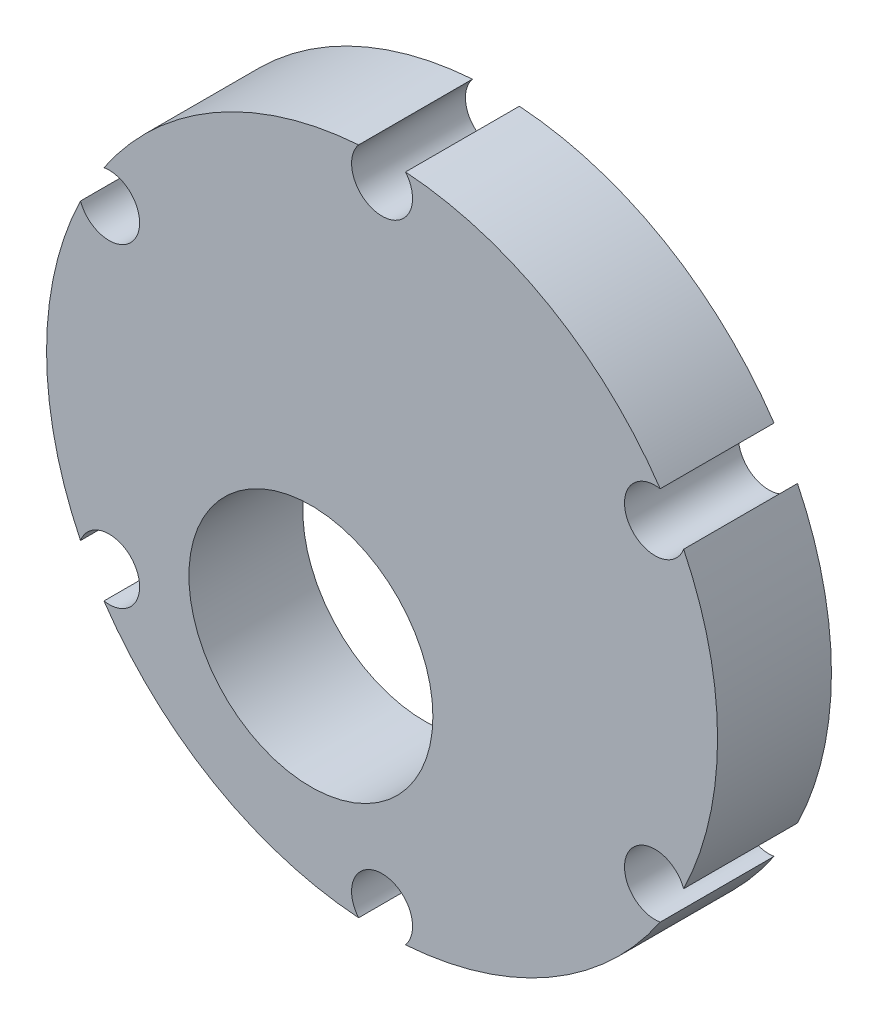
SolidWorks part; units mm, degrees
ref_plane "Front Plane" through (0, 0, 0) normal (0, 0, 1) x (1, 0, 0)
ref_plane "Top Plane" through (0, 0, 0) normal (0, 1, 0) x (1, 0, 0)
ref_plane "Right Plane" through (0, 0, 0) normal (1, 0, 0) x (0, 0, -1)
sketch "Sketch1" plane through (0, 0, 0) normal (0, 0, 1) x (1, 0, 0)
  circle A0 centre (0, 0) radius 16.5
  dimension "D1" = 33
extrude "Boss-Extrude1" add sketch "Sketch1" along normal blind 5.6
sketch "Sketch2" plane through (0, 0, 5.6) normal (0, 0, 1) x (1, 0, 0)
  circle A0 centre (0, 15.5) radius 1.5
  circle A1 centre (13.4234, 7.75) radius 1.5
  circle A2 centre (13.4234, -7.75) radius 1.5
  circle A3 centre (0, -15.5) radius 1.5
  circle A4 centre (-13.4234, -7.75) radius 1.5
  circle A5 centre (-13.4234, 7.75) radius 1.5
  point P15 (0, 0)
  dimension "D1" = 3
  dimension "D2" = 15.5
  dimension "D3" = 6
extrude "Cut-Extrude1" cut sketch "Sketch2" against normal through all
sketch "Sketch3" plane through (0, 0, 5.6) normal (0, 0, 1) x (1, 0, 0)
  line L0 (-3.5, -6.0622) -> (0, 0) construction
  line L1 (0, 0) -> (0, -15.5) construction
  circle A0 centre (-3.5, -6.0622) radius 6
  dimension "D1" = 12
  dimension "D2" = 30
  dimension "D3" = 7
extrude "Cut-Extrude2" cut sketch "Sketch3" against normal through all
equation "\"smallPulleyTeeth\"= 15"
equation "\"largePulleyTeeth\"= 30"
equation "\"eighthThick\"= 2.9mm"
equation "\"sixteenthThick\" = 1.7mm"
equation "\"wheelEighthThick\"=3.0mm"
equation "\"quarterThick\"=5.6mm"
equation "\"OD\" = 150mm"
equation "\"puckAngle\" = 60.5deg"
equation "\"puckDiam\" = 76.5mm"
equation "\"axlePress\" = 5.8mm"
equation "\"D1@Boss-Extrude1\"=\"quarterThick\""
